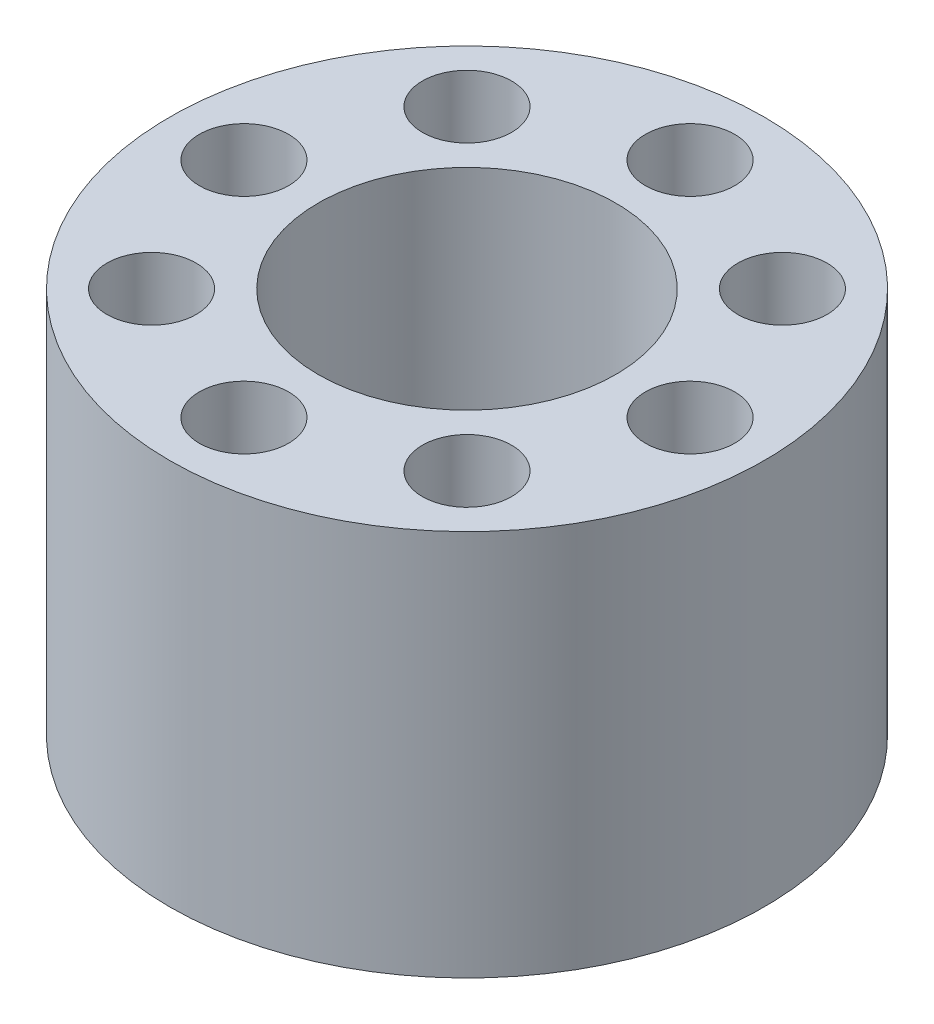
SolidWorks part; units mm, degrees
material "AISI 304"
ref_plane "前视基准面" through (0, 0, 0) normal (0, 0, 1) x (1, 0, 0)
ref_plane "上视基准面" through (0, 0, 0) normal (0, 1, 0) x (1, 0, 0)
ref_plane "右视基准面" through (0, 0, 0) normal (1, 0, 0) x (0, 0, -1)
sketch "草图2" plane through (0, 0, 0) normal (0, 0, 1) x (1, 0, 0)
  line L0 (0, 11.6326) -> (0, 0) construction
  line L1 (0, 0) -> (10, 0) construction
  line L3 (10, 0) -> (5, 0)
  line L4 (10, 0) -> (10, 13)
  line L5 (10, 13) -> (5, 13)
  line L6 (5, 0) -> (5, 13)
  dimension "D1" = 13
  dimension "D2" = 10
  dimension "D3" = 20
revolve "旋转1" add sketch "草图2" angle 360 about L0
sketch "草图3" plane through (0, 13, 0) normal (0, 1, 0) x (1, 0, 0)
  circle A0 centre (0, 0) radius 7.5 construction
  circle A1 centre (0, 7.5) radius 1.5
  circle A2 centre (5.3033, 5.3033) radius 1.5
  circle A3 centre (7.5, 0) radius 1.5
  circle A4 centre (5.3033, -5.3033) radius 1.5
  circle A5 centre (0, -7.5) radius 1.5
  circle A6 centre (-5.3033, -5.3033) radius 1.5
  circle A7 centre (-7.5, 0) radius 1.5
  circle A8 centre (-5.3033, 5.3033) radius 1.5
  dimension "D1" = 15
  dimension "D2" = 3
  dimension "D3" = 8
extrude "切除-拉伸1" cut sketch "草图3" against normal through all
